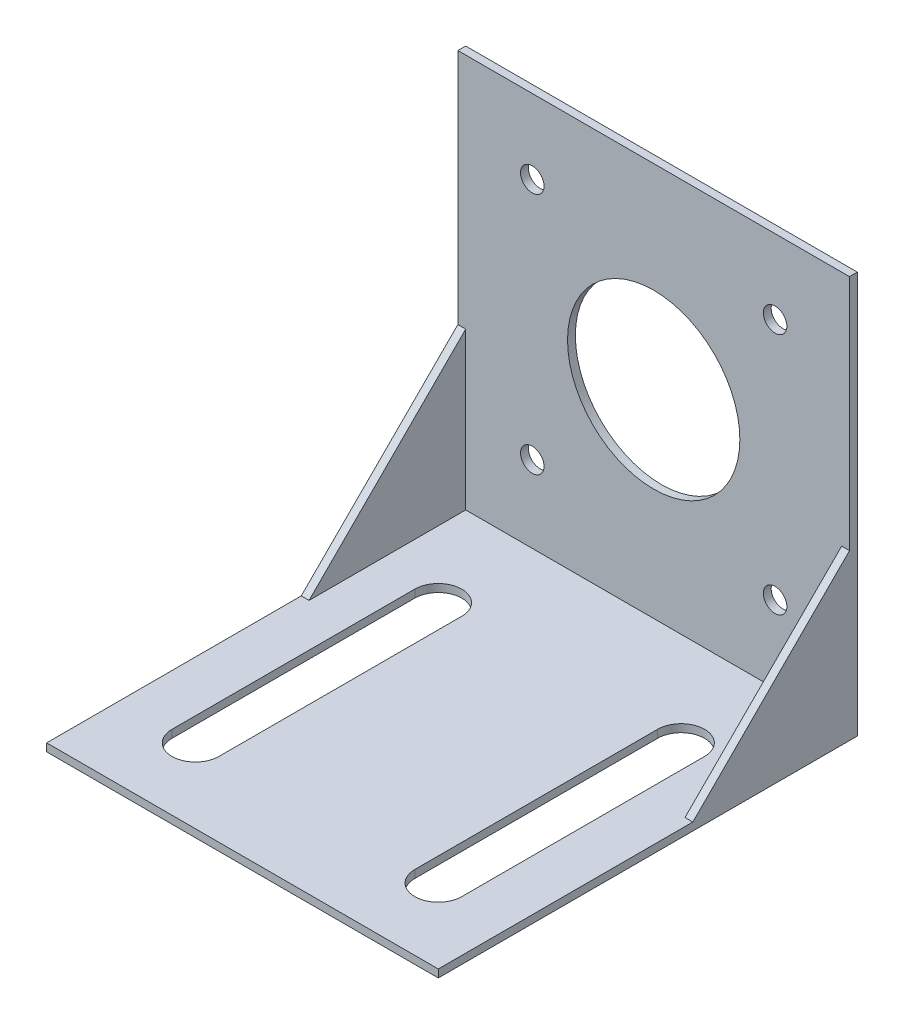
SolidWorks part; units mm, degrees
ref_plane "前视基准面" through (0, 0, 0) normal (0, 0, 1) x (1, 0, 0)
ref_plane "上视基准面" through (0, 0, 0) normal (0, 1, 0) x (1, 0, 0)
ref_plane "右视基准面" through (0, 0, 0) normal (1, 0, 0) x (0, 0, -1)
sketch "草图1" plane through (0, 0, 0) normal (0, 1, 0) x (1, 0, 0)
  line L0 (-15.5, -16.585) -> (-15.5, -17.25) construction
  line L1 (-25, 26.75) -> (25, 26.75)
  line L2 (-25, 26.75) -> (-25, -26.75)
  line L3 (-25, -26.75) -> (25, -26.75)
  line L4 (25, 26.75) -> (25, -26.75)
  line L5 (-25, 26.75) -> (25, -26.75) construction
  line L6 (-25, -26.75) -> (25, 26.75) construction
  line L8 (-18.5, 13.75) -> (-18.5, -17.25)
  line L9 (12.5, 13.75) -> (12.5, -17.25)
  line L10 (-12.5, 13.75) -> (-12.5, -17.25)
  line L11 (18.5, 13.75) -> (18.5, -17.25)
  arc A0 (-18.5, 13.75) -> (-12.5, 13.75) centre (-15.5, 13.75) cw
  arc A1 (-18.5, -17.25) -> (-12.5, -17.25) centre (-15.5, -17.25) ccw
  arc A2 (18.5, -17.25) -> (12.5, -17.25) centre (15.5, -17.25) cw
  arc A3 (18.5, 13.75) -> (12.5, 13.75) centre (15.5, 13.75) ccw
  point P0 (0, 0)
  point P6 (-15.5, -17.25)
  point P7 (15.5, -17.25)
  point P8 (-15.5, 13.75)
  point P9 (15.5, 9.47)
  dimension "D8" = 3
  dimension "D9" = 3
  dimension "D1" = 50
  dimension "D2" = 53.5
  dimension "D3" = 9.5
  dimension "D4" = 31
  dimension "D5" = 31
  dimension "D6" = 9.5
  dimension "D7" = 9.5
ref_plane "基准面1" through (0, 0, -26.75) normal (0, 0, 1) x (1, 0, 0)
sketch "草图2" plane through (0, 0, -26.75) normal (0, 0, 1) x (1, 0, 0)
  line L0 (25, 0) -> (-25, 0)
  line L1 (-25, 0) -> (-25, 51.3)
  line L2 (-25, 51.3) -> (25, 51.3)
  line L4 (25, 0) -> (25, 51.3)
  circle A0 centre (-15.5, 41.8) radius 1.5
  circle A1 centre (15.5, 41.8) radius 1.5
  circle A2 centre (-15.5, 10.8) radius 1.5
  circle A3 centre (15.5, 10.8) radius 1.5
  point P9 (-15.5, 41.8)
  point P10 (15.5, 41.8)
  point P12 (-15.5, 10.8)
  point P13 (15.5, 10.8)
  dimension "D6" = 31
  dimension "D1" = 51.3
  dimension "D2" = 9.5
  dimension "D3" = 9.5
  dimension "D4" = 31
  dimension "D5" = 9.5
extrude "凸台-拉伸1" add sketch "草图1" along normal blind 1
extrude "凸台-拉伸2" add sketch "草图2" along normal blind 1
ref_plane "基准面2" through (-25, 0, 0) normal (1, 0, 0) x (0, 0, -1)
sketch "草图4" plane through (-25, 0, 0) normal (1, 0, 0) x (0, 0, -1)
  line L0 (25.75, 51.3) -> (25.75, 1) construction
  line L1 (25.75, 1) -> (-26.75, 1) construction
  line L2 (25.75, 21) -> (5.75, 1)
  line L3 (5.75, 1) -> (25.75, 1)
  line L4 (25.75, 1) -> (25.75, 21)
  point P2 (25.75, 21)
  point P3 (5.75, 1)
  dimension "D1" = 20
  dimension "D2" = 20
extrude "凸台-拉伸3" add sketch "草图4" along normal blind 1
ref_plane "基准面5" through (25, 0, 0) normal (-1, 0, 0) x (0, 0, 1)
sketch "草图6" plane through (25, 0, 0) normal (-1, 0, 0) x (0, 0, 1)
  line L0 (-25.75, 1) -> (-25.75, 51.3) construction
  line L1 (26.75, 1) -> (-25.75, 1) construction
  line L2 (-25.75, 21) -> (-5.75, 1)
  line L3 (-5.75, 1) -> (-25.75, 1)
  line L4 (-25.75, 1) -> (-25.75, 21)
  point P0 (-25.75, 21)
  point P1 (-5.75, 1)
  dimension "D1" = 20
  dimension "D2" = 20
extrude "凸台-拉伸4" add sketch "草图6" along normal blind 1
sketch "草图7" plane through (0, 0, -25.75) normal (0, 0, 1) x (1, 0, 0)
  circle A0 centre (0, 26.3) radius 11
  point P8 (0, 26.3)
extrude "切除-拉伸1" cut sketch "草图7" against normal through all
